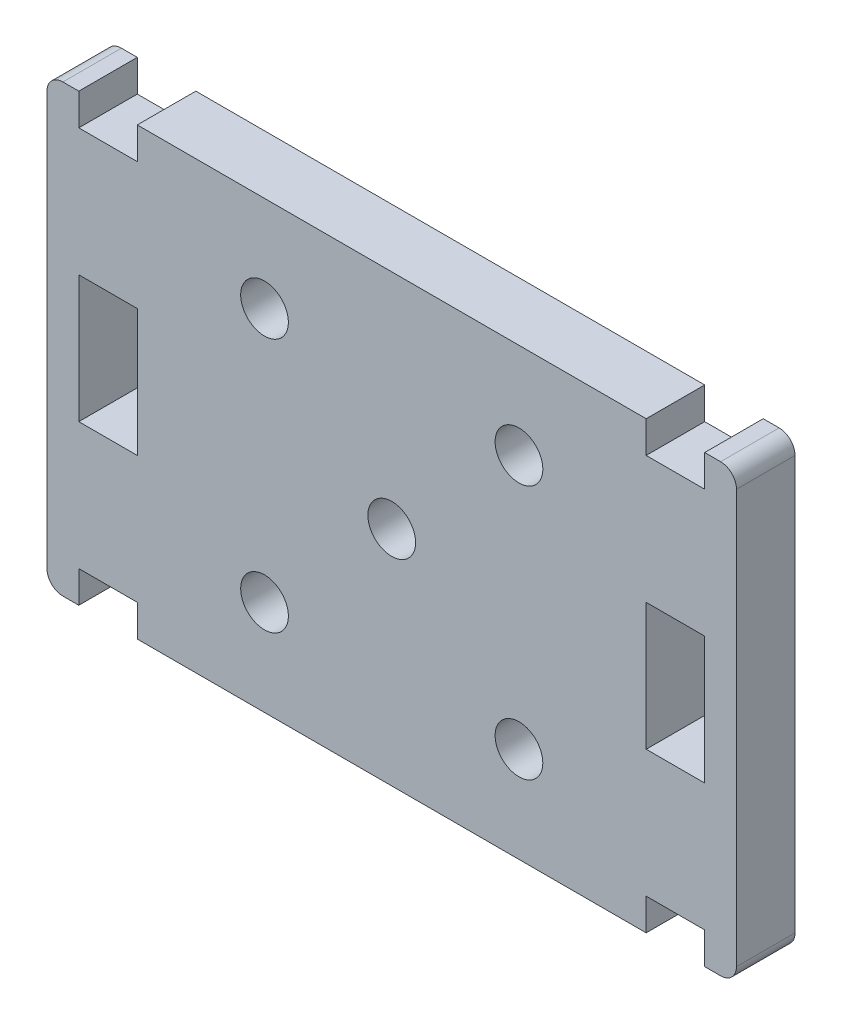
SolidWorks part; units mm, degrees
ref_plane "Front Plane" through (0, 0, 0) normal (0, 0, 1) x (1, 0, 0)
ref_plane "Top Plane" through (0, 0, 0) normal (0, 1, 0) x (1, 0, 0)
ref_plane "Right Plane" through (0, 0, 0) normal (1, 0, 0) x (0, 0, -1)
sketch "Sketch1" plane through (0, 0, 0) normal (0, 0, 1) x (1, 0, 0)
  line L0 (-25.4, 0) -> (25.4, 0) construction
  line L1 (-25.4, -22.225) -> (25.4, -22.225)
  line L2 (-25.4, -22.225) -> (-25.4, -19.05)
  line L3 (-25.4, 22.225) -> (25.4, 22.225)
  line L4 (25.4, -22.225) -> (25.4, -19.05)
  line L5 (-25.4, -22.225) -> (25.4, 22.225) construction
  line L6 (-25.4, 22.225) -> (25.4, -22.225) construction
  line L7 (0, -22.225) -> (0, 22.225) construction
  line L8 (31.242, -19.05) -> (25.4, -19.05)
  line L9 (31.242, 6.35) -> (25.4, 6.35)
  line L10 (31.242, 19.05) -> (31.242, 22.225)
  line L11 (31.242, 19.05) -> (25.4, 19.05)
  line L12 (25.4, -6.35) -> (25.4, 6.35)
  line L13 (31.242, 6.35) -> (25.4, 19.05) construction
  line L14 (31.242, 19.05) -> (25.4, 6.35) construction
  line L15 (31.242, -6.35) -> (31.242, 6.35)
  line L16 (31.242, -6.35) -> (25.4, -6.35)
  line L17 (25.4, 19.05) -> (25.4, 22.225)
  line L18 (34.417, -22.225) -> (31.242, -22.225)
  line L19 (34.417, -22.225) -> (34.417, 22.225)
  line L20 (34.417, 22.225) -> (31.242, 22.225)
  line L21 (31.242, -22.225) -> (31.242, -19.05)
  line L22 (34.417, -22.225) -> (31.242, 22.225) construction
  line L23 (34.417, 22.225) -> (31.242, -22.225) construction
  line L24 (-34.417, 22.225) -> (-31.242, -22.225) construction
  line L25 (-34.417, -22.225) -> (-31.242, 22.225) construction
  line L26 (-31.242, 19.05) -> (-25.4, 6.35) construction
  line L27 (-31.242, 6.35) -> (-25.4, 19.05) construction
  line L28 (-31.242, -22.225) -> (-31.242, -19.05)
  line L29 (-34.417, 22.225) -> (-31.242, 22.225)
  line L30 (-34.417, -22.225) -> (-34.417, 22.225)
  line L31 (-34.417, -22.225) -> (-31.242, -22.225)
  line L32 (-31.242, -6.35) -> (-25.4, -6.35)
  line L33 (-31.242, -6.35) -> (-31.242, 6.35)
  line L34 (-31.242, 19.05) -> (-25.4, 19.05)
  line L35 (-31.242, 19.05) -> (-31.242, 22.225)
  line L36 (-31.242, 6.35) -> (-25.4, 6.35)
  line L37 (-31.242, -19.05) -> (-25.4, -19.05)
  line L38 (-25.4, 19.05) -> (-25.4, 22.225)
  line L39 (-25.4, -6.35) -> (-25.4, 6.35)
  point P0 (0, 0)
  point P10 (28.321, 12.7)
  point P19 (32.8295, 0)
  point P36 (-32.8295, 0)
  point P37 (-28.321, 12.7)
  dimension "D1" = 50.8
  dimension "D2" = 44.45
  dimension "D3" = 5.842
  dimension "D4" = 12.7
  dimension "D5" = 12.7
  dimension "D6" = 3.175
extrude "Boss-Extrude1" add sketch "Sketch1" along normal blind 5.842
fillet "Fillet1" radius 1.5875 4 edges at (34.417, 22.225, 2.921) (34.417, -22.225, 2.921) (-34.417, -22.225, 2.921) (-34.417, 22.225, 2.921)
sketch "Sketch3" plane through (0, 0, 5.842) normal (0, 0, 1) x (1, 0, 0)
  line L0 (0, 22.225) -> (0, -22.225) construction
  line L1 (25.4, 22.225) -> (-25.4, 22.225) construction
  line L2 (-25.4, -22.225) -> (25.4, -22.225) construction
  line L3 (-34.417, 0) -> (34.417, 0) construction
  line L4 (-34.417, 20.6375) -> (-34.417, -20.6375) construction
  line L5 (34.417, -20.6375) -> (34.417, 20.6375) construction
  circle A0 centre (0, 0) radius 2.3813
  circle A1 centre (-12.7, 12.7) radius 2.3813
  circle A2 centre (-12.7, -12.7) radius 2.3813
  circle A3 centre (12.7, -12.7) radius 2.3813
  circle A4 centre (12.7, 12.7) radius 2.3813
  dimension "D1" = 4.7625
  dimension "D2" = 4.7625
  dimension "D3" = 12.7
  dimension "D4" = 12.7
extrude "Cut-Extrude2" cut sketch "Sketch3" against normal through all
